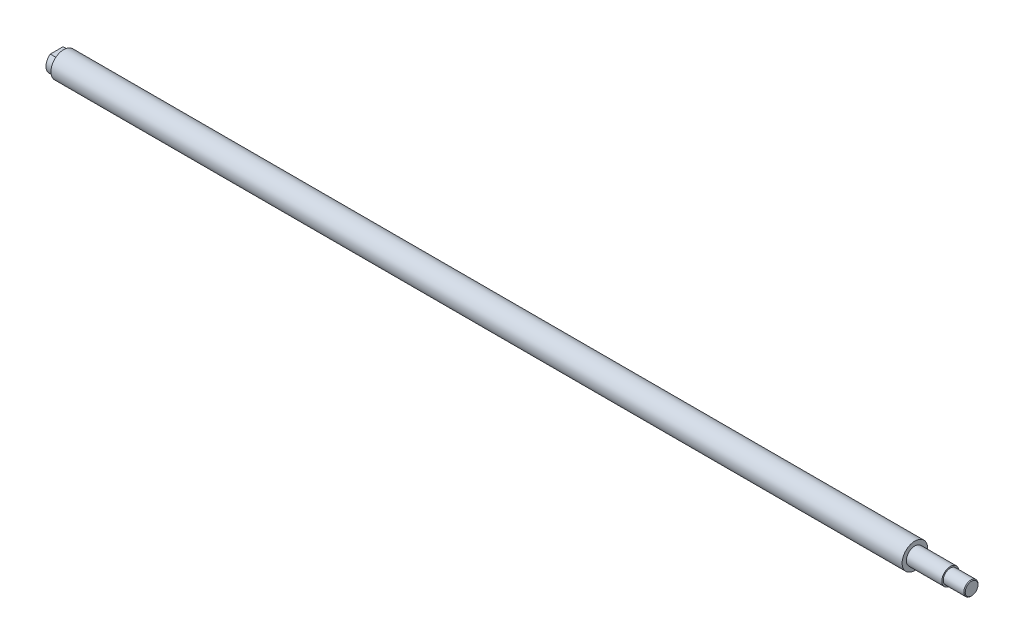
SolidWorks part; units mm, degrees
ref_plane "Front Plane" through (0, 0, 0) normal (0, 0, 1) x (1, 0, 0)
ref_plane "Top Plane" through (0, 0, 0) normal (0, 1, 0) x (1, 0, 0)
ref_plane "Right Plane" through (0, 0, 0) normal (1, 0, 0) x (0, 0, -1)
sketch "Sketch1" plane through (0, 0, 0) normal (0, 0, 1) x (1, 0, 0)
  line L0 (0, 0) -> (-640, 0)
  line L1 (-640, 0) -> (-640, 9)
  line L2 (-640, 9) -> (-40, 9)
  line L3 (0, 5) -> (0, 0)
  line L4 (-640, 0) -> (61.8592, 0) construction
  line L7 (0, 5) -> (-15, 5)
  line L8 (-15, 6) -> (-15, 5)
  line L11 (-15, 6) -> (-40, 6)
  line L12 (-40, 9) -> (-40, 6)
  dimension "D1" = 15
  dimension "D2" = 10
  dimension "D3" = 12
  dimension "D4" = 18
  dimension "D5" = 25
  dimension "D6" = 600
revolve "Revolve1" add sketch "Sketch1" angle 360 about L4
chamfer "Chamfer1" distance 0.5 angle 45 1 edges at (0, 0, 5)
sketch "Sketch2" plane through (-640, 0, 0) normal (-1, 0, 0) x (0, 0, 1)
  line L0 (-4.4857, 6.0107) -> (4.4857, 6.0107)
  arc A0 (-4.4857, 6.0107) -> (4.4857, 6.0107) centre (0, 0) ccw
extrude "Boss-Extrude1" add sketch "Sketch2" along normal blind 5
